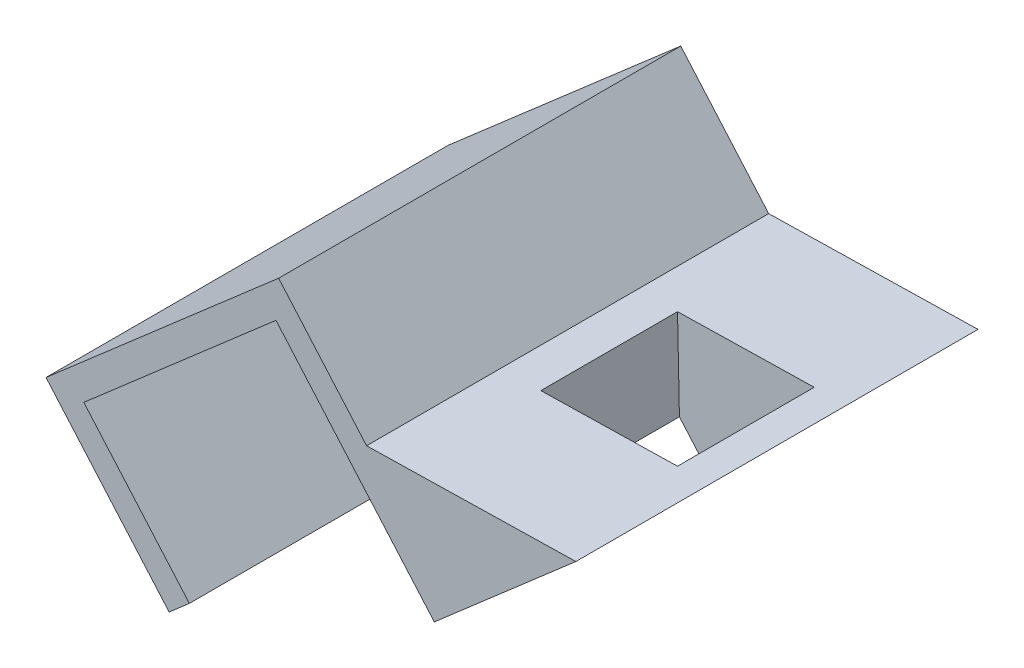
SolidWorks part; units mm, degrees
ref_plane "Front Plane" through (0, 0, 0) normal (0, 0, 1) x (1, 0, 0)
ref_plane "Top Plane" through (0, 0, 0) normal (0, 1, 0) x (1, 0, 0)
ref_plane "Right Plane" through (0, 0, 0) normal (1, 0, 0) x (0, 0, -1)
sketch "Sketch1" plane through (0, 0, 0) normal (0, 0, 1) x (1, 0, 0)
  line L0 (-70.9198, 0) -> (65.5432, 0) construction
  line L1 (-70.9198, 0) -> (-48.8778, 19.167)
  line L2 (-48.8778, 19.167) -> (-32.2108, 0)
  line L3 (-70.9198, 0) -> (-59.2529, -13.4169)
  dimension "D1" = 25.4
  dimension "D2" = 29.21
  dimension "D3" = 17.78
extrude "Extrude-Thin1" add sketch "Sketch1" along normal mid plane 38.1 thin
sketch "Sketch8" plane through (-13.869, 15.9494, 0) normal (0.6562, -0.7546, 0) x (0.7546, 0.6562, 0)
  line L1 (-24.3065, 19.05) -> (-9.0665, 19.05)
  line L2 (-24.3065, 19.05) -> (-24.3065, -19.05)
  line L3 (-24.3065, -19.05) -> (-9.0665, -19.05)
  line L4 (-9.0665, 19.05) -> (-9.0665, -19.05)
  dimension "D1" = 38.1
  dimension "D2" = 15.24
extrude "Boss-Extrude1" add sketch "Sketch8" against normal blind 12.7
sketch "Sketch9" plane through (0, 0, -19.05) normal (0, 0, -1) x (-1, 0, 0)
  line L0 (20.7106, 10.0002) -> (40.5443, 9.5835)
  line L1 (40.5443, 9.5835) -> (29.0441, 19.5837)
  line L2 (29.0441, 19.5837) -> (20.7106, 10.0002)
extrude "Cut-Extrude1" cut sketch "Sketch9" against normal through all both and the other way through all
sketch "Sketch10" plane through (-0.2191, 10.4307, 0) normal (-0.021, 0.9998, 0) x (0.9998, 0.021, 0)
  line L1 (-36.5241, -6.35) -> (-23.5701, -6.35)
  line L2 (-36.5241, -6.35) -> (-36.5241, 6.604)
  line L3 (-36.5241, 6.604) -> (-23.5701, 6.604)
  line L4 (-23.5701, -6.35) -> (-23.5701, 6.604)
  line L5 (-20.496, 19.05) -> (-40.3341, 19.05) construction
  line L8 (-40.3341, -19.05) -> (-40.3341, 19.05) construction
  dimension "D1" = 12.954
  dimension "D2" = 12.954
  dimension "D3" = 12.446
  dimension "D4" = 3.81
extrude "Cut-Extrude2" cut sketch "Sketch10" against normal up to next and the other way through all
